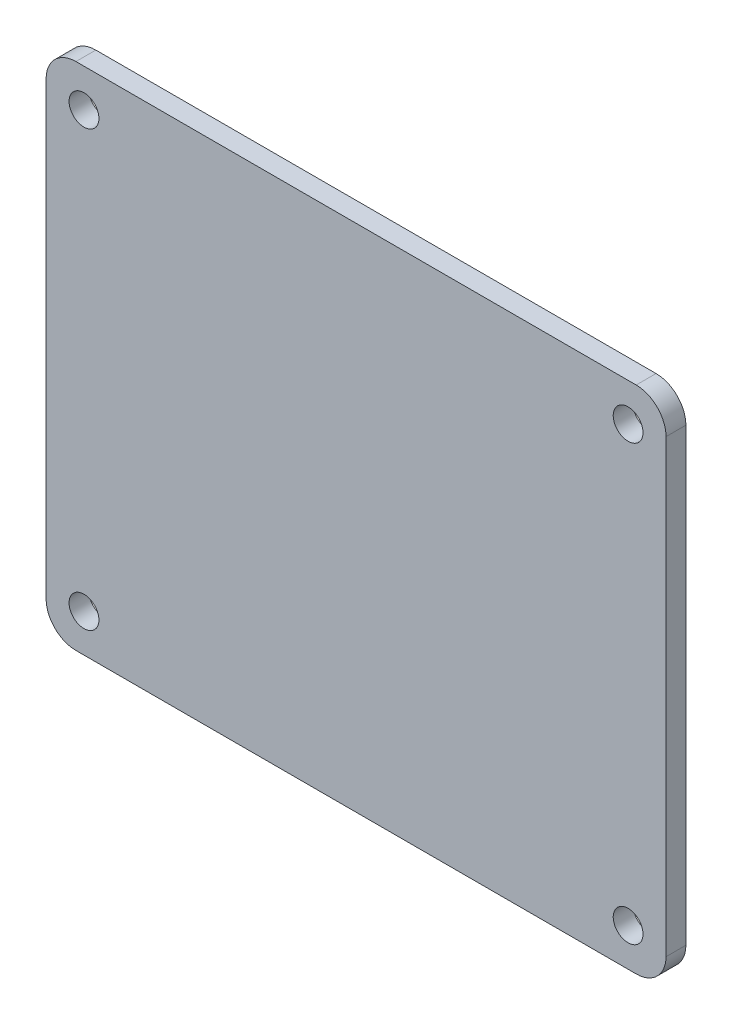
SolidWorks part; units mm, degrees
ref_plane "前视基准面" through (0, 0, 0) normal (0, 0, 1) x (1, 0, 0)
ref_plane "上视基准面" through (0, 0, 0) normal (0, 1, 0) x (1, 0, 0)
ref_plane "右视基准面" through (0, 0, 0) normal (1, 0, 0) x (0, 0, -1)
other "Configuration Table"
sketch "草图1" plane through (0, 0, 0) normal (0, 0, 1) x (1, 0, 0)
  line L1 (-23.6597, 12.547) -> (32.7003, 12.547)
  line L2 (-26.6597, 9.547) -> (-26.6597, -35.763)
  line L3 (-23.6597, -38.763) -> (32.7003, -38.763)
  line L4 (35.7003, 9.547) -> (35.7003, -35.763)
  arc A0 (32.7003, -38.763) -> (35.7003, -35.763) centre (32.7003, -35.763) ccw
  arc A1 (35.7003, 9.547) -> (32.7003, 12.547) centre (32.7003, 9.547) ccw
  arc A2 (-23.6597, -38.763) -> (-26.6597, -35.763) centre (-23.6597, -35.763) cw
  arc A3 (-26.6597, 9.547) -> (-23.6597, 12.547) centre (-23.6597, 9.547) cw
  point P8 (35.7003, 12.547)
  point P11 (-26.6597, -38.763)
  point P14 (-26.6597, 12.547)
  dimension "D3" = 3
  dimension "D1" = 62.36
  dimension "D2" = 51.31
extrude "凸台-拉伸2" add sketch "草图1" along normal blind 2 contours L1 A1 L4 A0 L3 A2 L2 A3
sketch "草图3" plane through (0, 0, 2) normal (0, 0, 1) x (1, 0, 0)
  line L0 (-26.6597, 9.547) -> (-26.6597, -35.763) construction
  line L1 (35.7003, 9.547) -> (35.7003, -35.763) construction
  line L2 (-23.6597, 12.547) -> (32.7003, 12.547) construction
  line L4 (-23.6597, -38.763) -> (32.7003, -38.763) construction
  circle A0 centre (-22.8497, 8.737) radius 1.5
  circle A1 centre (31.8903, 8.737) radius 1.5
  circle A2 centre (-22.8497, -34.953) radius 1.5
  circle A3 centre (31.8903, -34.953) radius 1.5
  point P0 (-22.8497, 8.737)
  point P1 (31.8903, 8.737)
  point P2 (-22.8497, -34.953)
  point P3 (31.8903, -34.953)
  dimension "D1" = 3.81
  dimension "D2" = 3.81
  dimension "D3" = 3.81
  dimension "D4" = 3.81
  dimension "D5" = 3.81
  dimension "D6" = 3.81
  dimension "D7" = 3.81
  dimension "D8" = 3.81
extrude "切除-拉伸1" cut sketch "草图3" against normal blind 2
